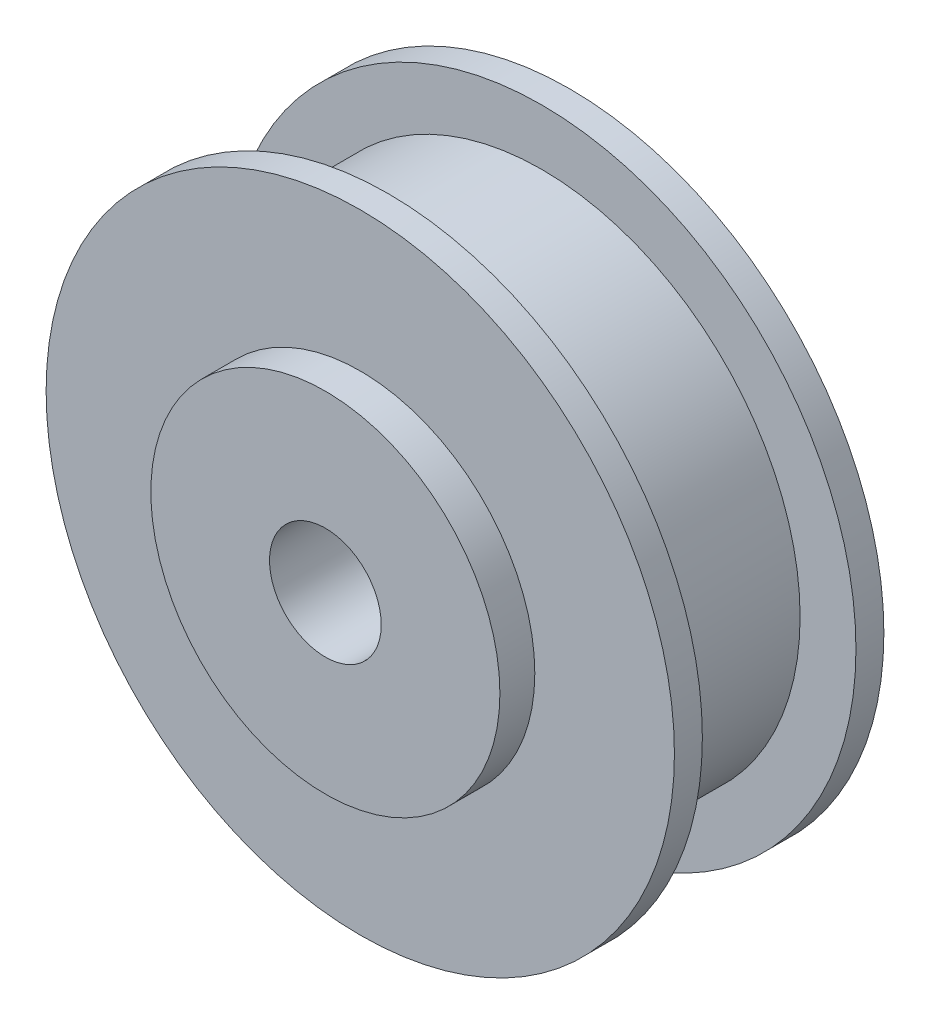
SolidWorks part; units mm, degrees
ref_plane "前视基准面" through (0, 0, 0) normal (0, 0, 1) x (1, 0, 0)
ref_plane "上视基准面" through (0, 0, 0) normal (0, 1, 0) x (1, 0, 0)
ref_plane "右视基准面" through (0, 0, 0) normal (1, 0, 0) x (0, 0, -1)
sketch "草图1" plane through (0, 0, 0) normal (0, 0, 1) x (1, 0, 0)
  circle A0 centre (0, 0) radius 22.5
  dimension "D1" = 45
extrude "凸台-拉伸1" add sketch "草图1" along normal blind 15
sketch "草图2" plane through (0, 0, 15) normal (0, 0, 1) x (1, 0, 0)
  circle A0 centre (0, 0) radius 12.5
  dimension "D1" = 25
extrude "凸台-拉伸2" add sketch "草图2" along normal blind 2.5
sketch "草图3" plane through (0, 0, 17.5) normal (0, 0, 1) x (1, 0, 0)
  circle A0 centre (0, 0) radius 4
  dimension "D1" = 8
extrude "切除-拉伸1" cut sketch "草图3" against normal blind 45
sketch "草图5" plane through (0, 0, 0) normal (0, 1, 0) x (1, 0, 0)
  line L0 (-22.5, -15) -> (22.5, -15) construction
  line L1 (18.5, -2) -> (22.5, -2)
  line L2 (18.5, -2) -> (18.5, -13)
  line L3 (18.5, -13) -> (22.5, -13)
  line L4 (22.5, -2) -> (22.5, -13)
  line L5 (22.5, -15) -> (22.5, 0) construction
  line L6 (0, 0) -> (0, -23.8767) construction
  dimension "D1" = 11
  dimension "D2" = 4
  dimension "D3" = 2
revolve "切除-旋转1" cut sketch "草图5" angle 360 about L6
